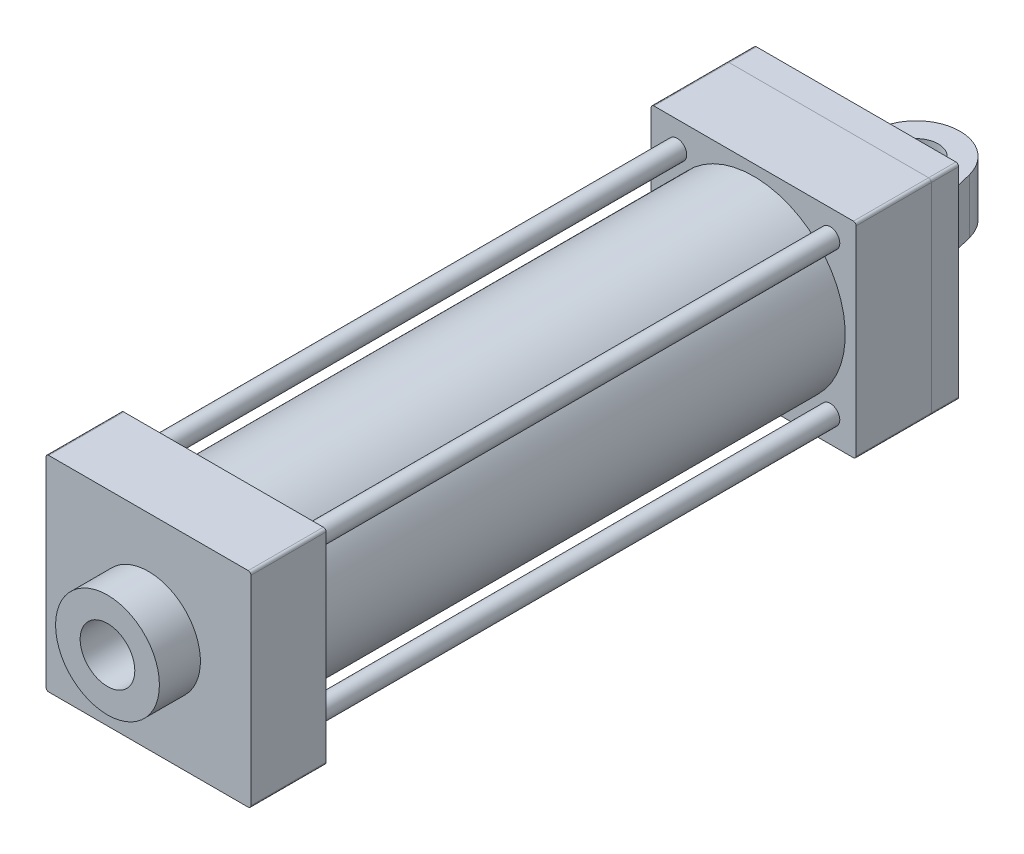
SolidWorks part; units mm, degrees
ref_plane "Front Plane" through (0, 0, 0) normal (0, 0, 1) x (1, 0, 0)
ref_plane "Top Plane" through (0, 0, 0) normal (0, 1, 0) x (1, 0, 0)
ref_plane "Right Plane" through (0, 0, 0) normal (1, 0, 0) x (0, 0, -1)
sketch "Sketch1" plane through (0, 0, 0) normal (0, 0, 1) x (1, 0, 0)
  line L1 (-37.5, -37.5) -> (37.5, -37.5)
  line L2 (-37.5, -37.5) -> (-37.5, 37.5)
  line L3 (-37.5, 37.5) -> (37.5, 37.5)
  line L4 (37.5, -37.5) -> (37.5, 37.5)
  line L5 (-37.5, -37.5) -> (37.5, 37.5) construction
  line L6 (-37.5, 37.5) -> (37.5, -37.5) construction
  point P0 (0, 0)
  dimension "D1" = 75
  dimension "D2" = 75
extrude "Boss-Extrude1" add sketch "Sketch1" along normal blind 27.5
sketch "Sketch2" plane through (0, 0, 27.5) normal (0, 0, 1) x (1, 0, 0)
  circle A0 centre (0, 0) radius 33.5
  dimension "D1" = 67
extrude "Boss-Extrude2" add sketch "Sketch2" along normal blind 194
sketch "Sketch3" plane through (0, 0, 221.5) normal (0, 0, 1) x (1, 0, 0)
  line L1 (-37.5, -37.5) -> (37.5, -37.5)
  line L2 (-37.5, -37.5) -> (-37.5, 37.5)
  line L3 (-37.5, 37.5) -> (37.5, 37.5)
  line L4 (37.5, -37.5) -> (37.5, 37.5)
  line L5 (-37.5, -37.5) -> (37.5, 37.5) construction
  line L6 (-37.5, 37.5) -> (37.5, -37.5) construction
  point P0 (0, 0)
extrude "Boss-Extrude3" add sketch "Sketch3" along normal blind 27.5
sketch "Sketch4" plane through (0, 0, 249) normal (0, 0, 1) x (1, 0, 0)
  line L1 (-28, -28) -> (28, -28) construction
  line L2 (-28, -28) -> (-28, 28) construction
  line L3 (-28, 28) -> (28, 28) construction
  line L4 (28, -28) -> (28, 28) construction
  line L5 (-28, -28) -> (28, 28) construction
  line L6 (-28, 28) -> (28, -28) construction
  circle A0 centre (-28, 28) radius 3.5
  circle A1 centre (28, 28) radius 3.5
  circle A2 centre (28, -28) radius 3.5
  circle A3 centre (-28, -28) radius 3.5
  point P0 (0, 0)
  dimension "D3" = 7
  dimension "D1" = 56
  dimension "D2" = 56
extrude "Boss-Extrude4" add sketch "Sketch4" against normal blind 234.5
sketch "Sketch5" plane through (0, 0, 0) normal (0, 0, -1) x (-1, 0, 0)
  line L1 (-28, -28) -> (28, -28) construction
  line L2 (-28, -28) -> (-28, 28) construction
  line L3 (-28, 28) -> (28, 28) construction
  line L4 (28, -28) -> (28, 28) construction
  line L5 (-28, -28) -> (28, 28) construction
  line L6 (-28, 28) -> (28, -28) construction
  circle A0 centre (-28, 28) radius 4
  circle A1 centre (28, 28) radius 4
  circle A2 centre (28, -28) radius 4
  circle A3 centre (-28, -28) radius 4
  point P0 (0, 0)
  dimension "D3" = 8
  dimension "D1" = 56
  dimension "D2" = 56
extrude "Cut-Extrude1" cut sketch "Sketch5" against normal blind 19.5
fillet "Fillet1" radius 1 8 edges at (-37.5, 37.5, 13.75) (-37.5, -37.5, 13.75) (-37.5, 37.5, 235.25) (-37.5, -37.5, 235.25) (37.5, -37.5, 235.25) (37.5, 37.5, 235.25) (37.5, -37.5, 13.75) (37.5, 37.5, 13.75)
sketch "Sketch6" plane through (0, 0, 249) normal (0, 0, 1) x (1, 0, 0)
  circle A0 centre (0, 0) radius 19
  dimension "D1" = 38
extrude "Boss-Extrude5" add sketch "Sketch6" along normal blind 15
sketch "Sketch7" plane through (0, 0, 264) normal (0, 0, 1) x (1, 0, 0)
  circle A0 centre (0, 0) radius 10
  dimension "D1" = 20
extrude "Cut-Extrude2" cut sketch "Sketch7" against normal blind 300
sketch "Sketch9" plane through (0, 0, 0) normal (0, 0, -1) x (-1, 0, 0)
  line L4 (37.5, -36.5) -> (37.5, 36.5)
  line L5 (36.5, 37.5) -> (-36.5, 37.5)
  line L6 (-37.5, 36.5) -> (-37.5, -36.5)
  line L7 (-36.5, -37.5) -> (36.5, -37.5)
  line L8 (37.5, -36.5) -> (37.5, 36.5)
  line L9 (36.5, 37.5) -> (-36.5, 37.5)
  line L10 (-37.5, 36.5) -> (-37.5, -36.5)
  line L11 (-36.5, -37.5) -> (36.5, -37.5)
  circle A0 centre (-28, 28) radius 4 construction
  circle A1 centre (28, 28) radius 4 construction
  circle A2 centre (28, -28) radius 4 construction
  circle A3 centre (-28, -28) radius 4 construction
  arc A4 (37.5, 36.5) -> (36.5, 37.5) centre (36.5, 36.5) ccw
  arc A5 (-36.5, 37.5) -> (-37.5, 36.5) centre (-36.5, 36.5) ccw
  arc A6 (-37.5, -36.5) -> (-36.5, -37.5) centre (-36.5, -36.5) ccw
  arc A7 (36.5, -37.5) -> (37.5, -36.5) centre (36.5, -36.5) ccw
  arc A8 (37.5, 36.5) -> (36.5, 37.5) centre (36.5, 36.5) ccw
  arc A9 (-36.5, 37.5) -> (-37.5, 36.5) centre (-36.5, 36.5) ccw
  arc A10 (-37.5, -36.5) -> (-36.5, -37.5) centre (-36.5, -36.5) ccw
  arc A11 (36.5, -37.5) -> (37.5, -36.5) centre (36.5, -36.5) ccw
  circle A12 centre (-28, 28) radius 4
  circle A13 centre (28, 28) radius 4
  circle A14 centre (28, -28) radius 4
  circle A15 centre (-28, -28) radius 4
  dimension "D1" = 0
extrude "Boss-Extrude6" add sketch "Sketch9" along normal blind 10 separate body
sketch "Sketch10" plane through (0, 0, 0) normal (0, 1, 0) x (1, 0, 0)
  line L0 (0, 10) -> (0, 32) construction
  line L1 (-36.5, 10) -> (36.5, 10) construction
  line L2 (-22, 10) -> (-15.5212, 35.8848)
  line L3 (22, 10) -> (15.5212, 35.8848)
  line L4 (-22, 10) -> (22, 10)
  line L5 (0, 32) -> (0, 48) construction
  arc A0 (15.5212, 35.8848) -> (-15.5212, 35.8848) centre (0, 32) ccw
  circle A1 centre (0, 32) radius 8
  dimension "D3" = 16
  dimension "D4" = 16
  dimension "D1" = 22
  dimension "D2" = 22
extrude "Boss-Extrude7" add sketch "Sketch10" along normal blind 10 and the other way blind 10 separate body
